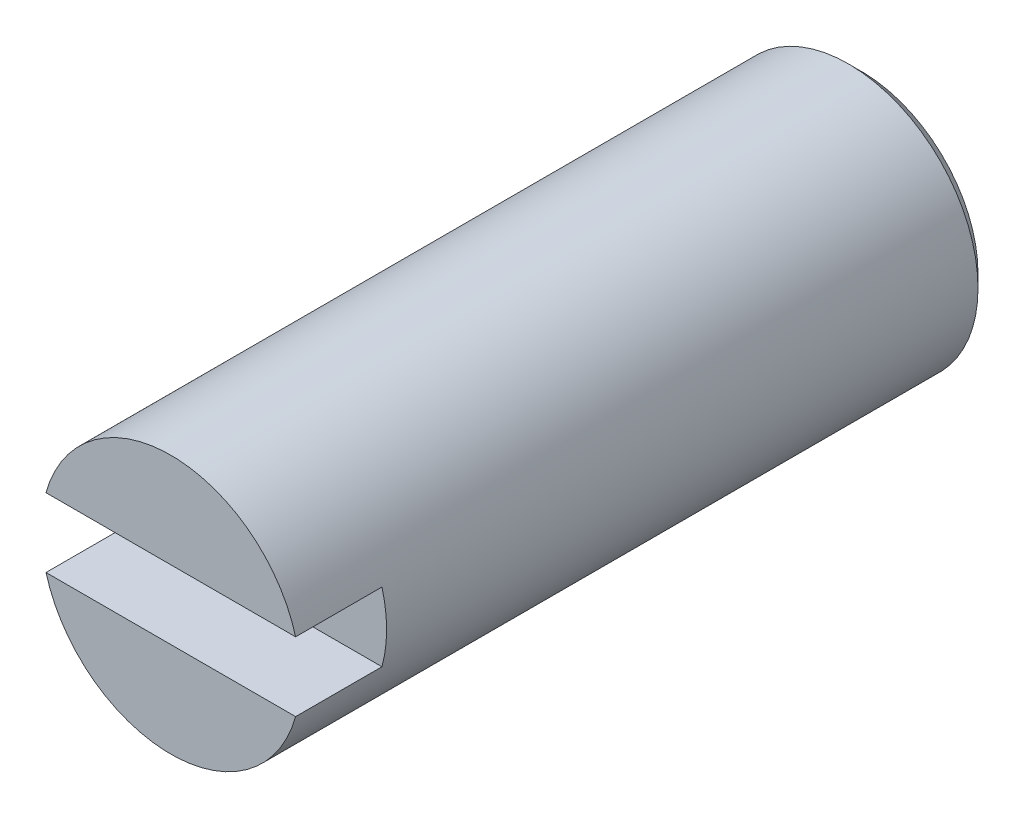
SolidWorks part; units mm, degrees
material "AISI 304"
ref_plane "Front Plane" through (0, 0, 0) normal (0, 0, 1) x (1, 0, 0)
ref_plane "Top Plane" through (0, 0, 0) normal (0, 1, 0) x (1, 0, 0)
ref_plane "Right Plane" through (0, 0, 0) normal (1, 0, 0) x (0, 0, -1)
sketch "Sketch1" plane through (0, 0, 0) normal (0, 0, 1) x (1, 0, 0)
  circle A0 centre (0, 0) radius 1.5
  dimension "D1" = 3
extrude "Boss-Extrude1" add sketch "Sketch1" along normal mid plane 8 contours A0
cosmetic thread "Cosmetic Thread1" parameters "D2"=2.439
chamfer "Chamfer1" distance 0.15 angle 45 1 edges at (1.5, 0, -4)
sketch "Sketch3" plane through (0, 0, 4) normal (0, 0, 1) x (1, 0, 0)
  line L0 (1.65, 0) -> (-1.65, 0) construction
  line L1 (1.5, -0.4) -> (-1.5, -0.4)
  line L2 (1.5, -0.4) -> (1.5, 0.4)
  line L3 (1.5, 0.4) -> (-1.5, 0.4)
  line L4 (-1.5, -0.4) -> (-1.5, 0.4)
  line L5 (1.5, -0.4) -> (-1.5, 0.4) construction
  line L6 (1.5, 0.4) -> (-1.5, -0.4) construction
  circle A0 centre (0, 0) radius 1.5 construction
  point P0 (0, 0)
  dimension "D1" = 0.8
extrude "Cut-Extrude1" cut sketch "Sketch3" against normal blind 1 contours L3 L4 L1 L2
